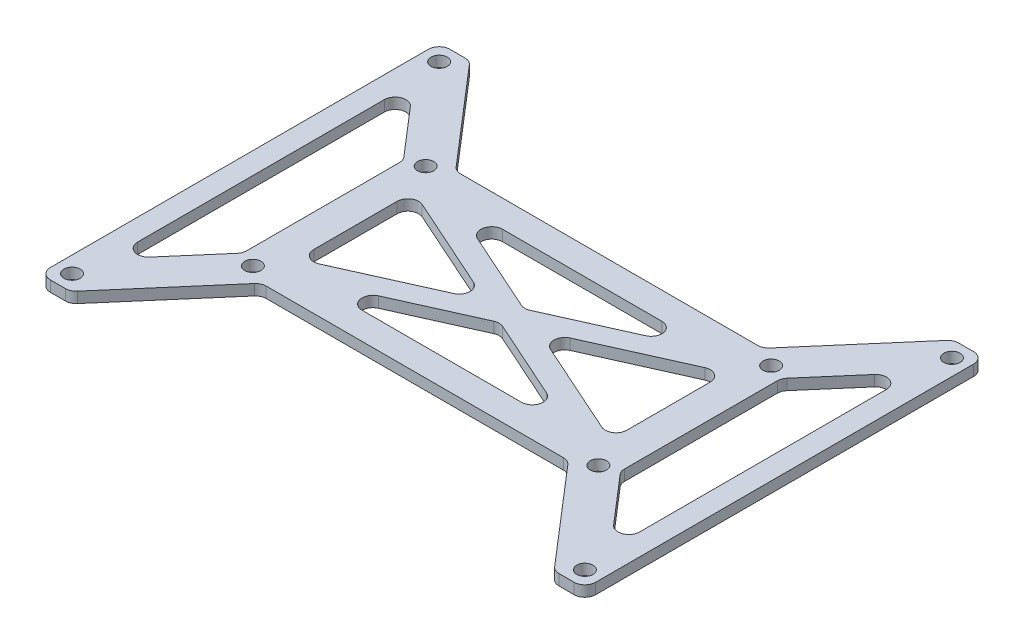
SolidWorks part; units mm, degrees
material "环氧玻璃布层压板"
ref_plane "前视基准面" through (0, 0, 0) normal (0, 0, 1) x (1, 0, 0)
ref_plane "上视基准面" through (0, 0, 0) normal (0, 1, 0) x (1, 0, 0)
ref_plane "右视基准面" through (0, 0, 0) normal (1, 0, 0) x (0, 0, -1)
sketch "草图1" plane through (0, 0, 0) normal (0, 1, 0) x (1, 0, 0)
  line L0 (-50.5, -37) -> (-50.5, 37)
  line L1 (-32, -16) -> (32, -16) construction
  line L2 (-32, -16) -> (-32, 16) construction
  line L3 (-32, 16) -> (32, 16) construction
  line L4 (32, -16) -> (32, 16) construction
  line L5 (0, 16) -> (0, -16) construction
  line L6 (-32, 0) -> (32, 0) construction
  line L7 (-42.5, -29) -> (42.5, -29) construction
  line L8 (-42.5, -29) -> (-42.5, 29) construction
  line L9 (-42.5, 29) -> (42.5, 29) construction
  line L10 (42.5, -29) -> (42.5, 29) construction
  line L11 (0, 29) -> (0, -29) construction
  line L12 (-42.5, 0) -> (42.5, 0) construction
  line L13 (-50.5, 37) -> (50.5, 37)
  line L14 (50.5, -37) -> (50.5, 37)
  line L15 (-50.5, -37) -> (50.5, -37)
  line L16 (-47.5, -34) -> (-47.5, 34) construction
  line L17 (-47.5, 34) -> (47.5, 34) construction
  line L18 (47.5, -34) -> (47.5, 34) construction
  line L19 (-47.5, -34) -> (47.5, -34) construction
  circle A0 centre (32, -16) radius 1.5
  circle A1 centre (32, 16) radius 1.5
  circle A2 centre (-32, 16) radius 1.5
  circle A3 centre (-32, -16) radius 1.5
  circle A4 centre (47.5, 34) radius 1.5
  circle A5 centre (-47.5, 34) radius 1.5
  circle A6 centre (-47.5, -34) radius 1.5
  circle A7 centre (47.5, -34) radius 1.5
  point P0 (0, 0)
  point P8 (0, 0)
  dimension "D6" = 3
  dimension "D8" = 3
  dimension "D1" = 32
  dimension "D2" = 64
  dimension "D3" = 58
  dimension "D4" = 85
  dimension "D5" = 8
  dimension "D7" = 3
extrude "凸台-拉伸1" add sketch "草图1" along normal blind 2
sketch "草图2" plane through (0, 2, 0) normal (0, 1, 0) x (1, 0, 0)
  line L1 (-29, -13) -> (29, -13)
  line L2 (-29, -13) -> (-29, 13)
  line L3 (-29, 13) -> (29, 13)
  line L4 (29, -13) -> (29, 13)
  line L5 (0, 13) -> (0, -13) construction
  line L6 (-29, 0) -> (29, 0) construction
  circle A0 centre (32, 16) radius 1.5 construction
  point P0 (0, 0)
  dimension "D1" = 3
  dimension "D2" = 3
extrude "切除-拉伸1" cut sketch "草图2" against normal blind 2
sketch "草图3" plane through (0, 2, 0) normal (0, 1, 0) x (1, 0, 0)
  line L0 (-47.5, 34) -> (-32, 16) construction
  line L1 (-44.8047, 37) -> (-28.4436, 18)
  line L2 (50.5, 37) -> (-50.5, 37) construction
  line L3 (-28.4436, 18) -> (28.4436, 18)
  line L4 (28.4436, 18) -> (44.8047, 37)
  line L5 (44.8047, 37) -> (-44.8047, 37)
  line L6 (29, 13) -> (-29, 13) construction
  line L7 (0, 37) -> (0, 0) construction
  point P15 (25.8291, 18)
  dimension "D1" = 4
  dimension "D2" = 5
extrude "切除-拉伸2" cut sketch "草图3" against normal blind 2
mirror "镜向1" about plane through (0, 0, 0) normal (0, 0, 1) of "切除-拉伸2"
sketch "草图4" plane through (0, 2, 0) normal (0, 1, 0) x (1, 0, 0)
  line L0 (-29, 13) -> (29, -13) construction
  line L1 (29, 13) -> (-29, -13) construction
  line L2 (-29.8181, 11.175) -> (28.1819, -14.825)
  line L3 (28.1819, 14.825) -> (-29.8181, -11.175)
  line L4 (-28.1819, 14.825) -> (29.8181, -11.175)
  line L5 (29.8181, 11.175) -> (-28.1819, -14.825)
  line L6 (-29.8181, 11.175) -> (-28.1819, 14.825)
  line L7 (28.1819, -14.825) -> (29.8181, -11.175)
  line L8 (28.1819, 14.825) -> (29.8181, 11.175)
  line L9 (-29.8181, -11.175) -> (-28.1819, -14.825)
  line M1 (29, 13) -> (29, -13)
  line M2 (29, -13) -> (-29, -13)
  line M3 (-29, -13) -> (-29, 13)
  line M4 (-29, 13) -> (29, 13)
  dimension "D1" = 2
  dimension "D2" = 2
extrude "凸台-拉伸2" add sketch "草图4" against normal blind 2 contours L5 L2 L3 M3 M2 | L4 L2 L3 M4 M3 | L5 L4 L3 L2 | L5 L3 L4 M1 M4 | L4 L5 L2 M2 M1
sketch "草图5" plane through (0, 0, 0) normal (0, -1, 0) x (1, 0, 0)
  line L0 (-47.5, 34) -> (-32, 16) construction
  line L1 (-46.5, 28.2412) -> (-35, 14.8863)
  line L2 (-35, 14.8863) -> (-35, -14.8863)
  line L3 (-35, -14.8863) -> (-46.5, -28.2412)
  line L4 (-46.5, -28.2412) -> (-46.5, 28.2412)
  line L5 (-50.5, -37) -> (-50.5, 37) construction
  line L6 (0, 0) -> (-64.4184, 0) construction
  circle A0 centre (-32, 16) radius 1.5 construction
  dimension "D1" = 4
  dimension "D2" = 3
  dimension "D3" = 3
extrude "切除-拉伸3" cut sketch "草图5" against normal blind 2
mirror "镜向2" about plane through (0, 0, 0) normal (1, 0, 0) of "切除-拉伸3"
fillet "圆角1" radius 2 32 edges at (-28.4436, 1, 18) (28.4436, 1, 18) (50.5, 1, 37) (50.5, 1, -37) (44.8047, 1, -37) (28.4436, 1, -18) (-28.4436, 1, -18) (-44.8047, 1, -37) (-50.5, 1, -37) (-50.5, 1, 37) (-44.8047, 1, 37) (44.8047, 1, 37) (35, 1, -14.8863) (46.5, 1, -28.2412) (0, 1, -2.1918) (24.1107, 1, -13) (-24.1107, 1, -13) (-4.8893, 1, 0) (-29, 1, -10.8082) (-29, 1, 10.8082) (0, 1, 2.1918) (-24.1107, 1, 13) (24.1107, 1, 13) (4.8893, 1, 0) (29, 1, 10.8082) (29, 1, -10.8082) (-46.5, 1, 28.2412) (-35, 1, 14.8863) (-35, 1, -14.8863) (-46.5, 1, -28.2412) (46.5, 1, 28.2412) (35, 1, 14.8863)
